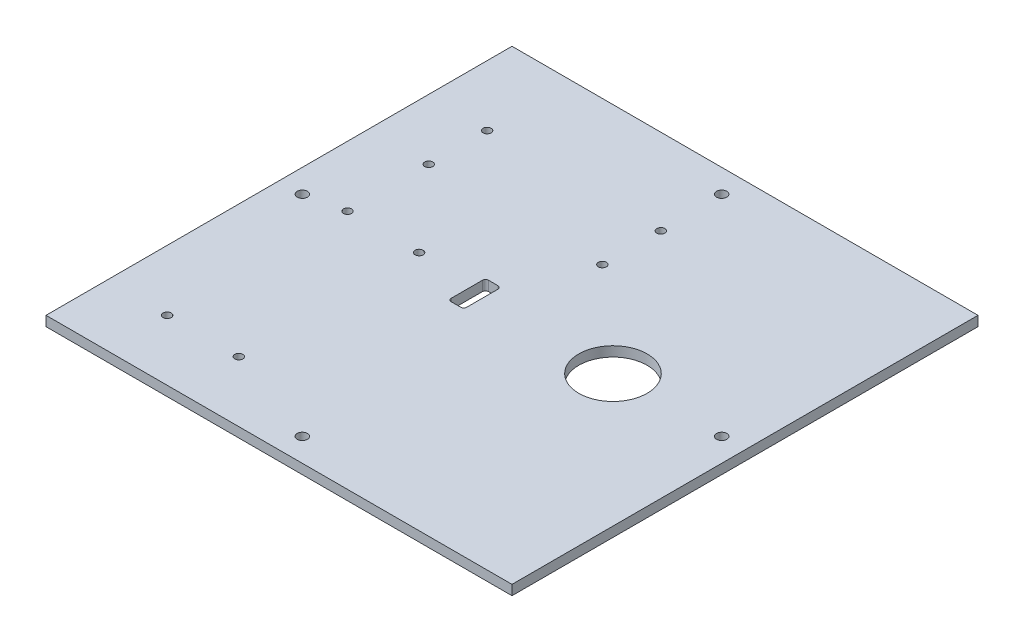
SolidWorks part; units mm, degrees
ref_plane "Front Plane" through (0, 0, 0) normal (0, 0, 1) x (1, 0, 0)
ref_plane "Top Plane" through (0, 0, 0) normal (0, 1, 0) x (1, 0, 0)
ref_plane "Right Plane" through (0, 0, 0) normal (1, 0, 0) x (0, 0, -1)
sketch "Sketch1" plane through (0, 0, 0) normal (0, 1, 0) x (1, 0, 0)
  line L1 (-75, 75) -> (75, 75)
  line L2 (-75, 75) -> (-75, -75)
  line L3 (-75, -75) -> (75, -75)
  line L4 (75, 75) -> (75, -75)
  line L5 (-75, 75) -> (75, -75) construction
  line L6 (-75, -75) -> (75, 75) construction
  line L7 (-67.5, 67.5) -> (67.5, 67.5) construction
  line L8 (-67.5, 67.5) -> (-67.5, -67.5) construction
  line L9 (-67.5, -67.5) -> (67.5, -67.5) construction
  line L10 (67.5, 67.5) -> (67.5, -67.5) construction
  line L11 (-67.5, 67.5) -> (67.5, -67.5) construction
  line L12 (-67.5, -67.5) -> (67.5, 67.5) construction
  line L13 (-55.5, -55.5) -> (-32.45, -55.5) construction
  line L14 (-55.5, -55.5) -> (-55.5, 2.55) construction
  line L15 (-55.5, 2.55) -> (-32.45, 2.55) construction
  line L16 (-32.45, -55.5) -> (-32.45, 2.55) construction
  line L17 (-55.5, 47.5) -> (0.4, 47.5) construction
  line L18 (-55.5, 47.5) -> (-55.5, 28.7) construction
  line L19 (-55.5, 28.7) -> (0.4, 28.7) construction
  line L20 (0.4, 47.5) -> (0.4, 28.7) construction
  line L21 (-13.5343, -6) -> (-10.5343, -6)
  line L22 (-14.5343, -5) -> (-14.5343, 5)
  line L23 (-13.5343, 6) -> (-10.5343, 6)
  line L24 (-9.5343, -5) -> (-9.5343, 5)
  circle A0 centre (-67.5, 0) radius 1.65
  circle A1 centre (0, 67.5) radius 1.65
  circle A2 centre (67.5, 0) radius 1.65
  circle A3 centre (0, -67.5) radius 1.65
  circle A5 centre (-55.5, -55.5) radius 1.3
  circle A6 centre (-32.45, -55.5) radius 1.3
  circle A7 centre (-32.45, 2.55) radius 1.3
  circle A8 centre (-55.5, 2.55) radius 1.3
  circle A9 centre (0.4, 47.5) radius 1.3
  circle A10 centre (0.4, 28.7) radius 1.3
  circle A11 centre (-55.5, 47.5) radius 1.3
  circle A12 centre (-55.5, 28.7) radius 1.3
  circle A13 centre (32.5, 0) radius 11
  arc A14 (-13.5343, -6) -> (-14.5343, -5) centre (-13.5343, -5) cw
  arc A15 (-10.5343, -6) -> (-9.5343, -5) centre (-10.5343, -5) ccw
  arc A16 (-10.5343, 6) -> (-9.5343, 5) centre (-10.5343, 5) cw
  arc A17 (-14.5343, 5) -> (-13.5343, 6) centre (-13.5343, 5) cw
  point P0 (0, 0)
  point P6 (0, 0)
  point P41 (-9.5343, 0)
  point P44 (-14.5343, -6)
  point P47 (-9.5343, -6)
  point P52 (-14.5343, 6)
  dimension "D5" = 3.3
  dimension "D6" = 22
  dimension "D9" = 2.6
  dimension "D13" = 2.6
  dimension "D17" = 35
  dimension "D18" = 5
  dimension "D20" = 1
  dimension "D1" = 7.5
  dimension "D2" = 7.5
  dimension "D3" = 150
  dimension "D4" = 150
  dimension "D7" = 58.05
  dimension "D8" = 23.05
  dimension "D10" = 12
  dimension "D11" = 12
  dimension "D12" = 55.9
  dimension "D14" = 18.8
  dimension "D15" = 20
  dimension "D16" = 12
  dimension "D19" = 12
extrude "Boss-Extrude1" add sketch "Sketch1" along normal blind 3.175
